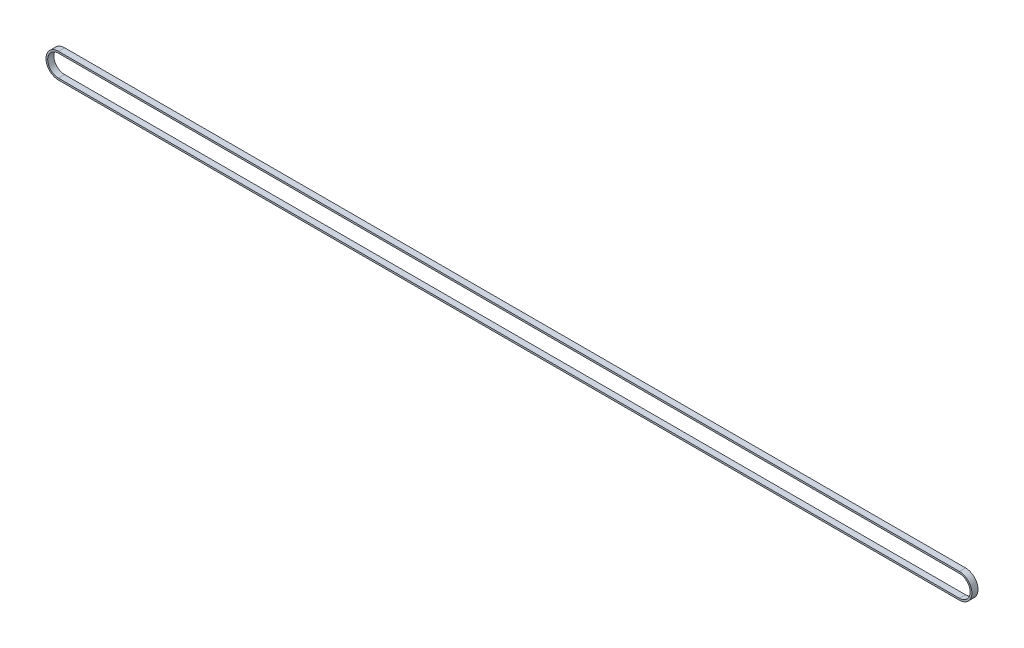
SolidWorks part; units mm, degrees
material "Rubber"
ref_plane "Front Plane" through (0, 0, 0) normal (0, 0, 1) x (1, 0, 0)
ref_plane "Top Plane" through (0, 0, 0) normal (0, 1, 0) x (1, 0, 0)
ref_plane "Right Plane" through (0, 0, 0) normal (1, 0, 0) x (0, 0, -1)
sketch "Sketch1" plane through (0, 0, 0) normal (0, 0, 1) x (1, 0, 0)
  line L0 (0, 0) -> (732, 0) construction
  line L1 (0, 8.75) -> (732, 8.75)
  line L2 (732, -8.75) -> (0, -8.75)
  arc A0 (0, 8.75) -> (0, -8.75) centre (0, 0) ccw
  arc A1 (732, -8.75) -> (732, 8.75) centre (732, 0) ccw
  dimension "D1" = 17.5
  dimension "D2" = 732
extrude "Extrude-Thin1" add sketch "Sketch1" along normal mid plane 5 thin thin type one direction wall 1.38
